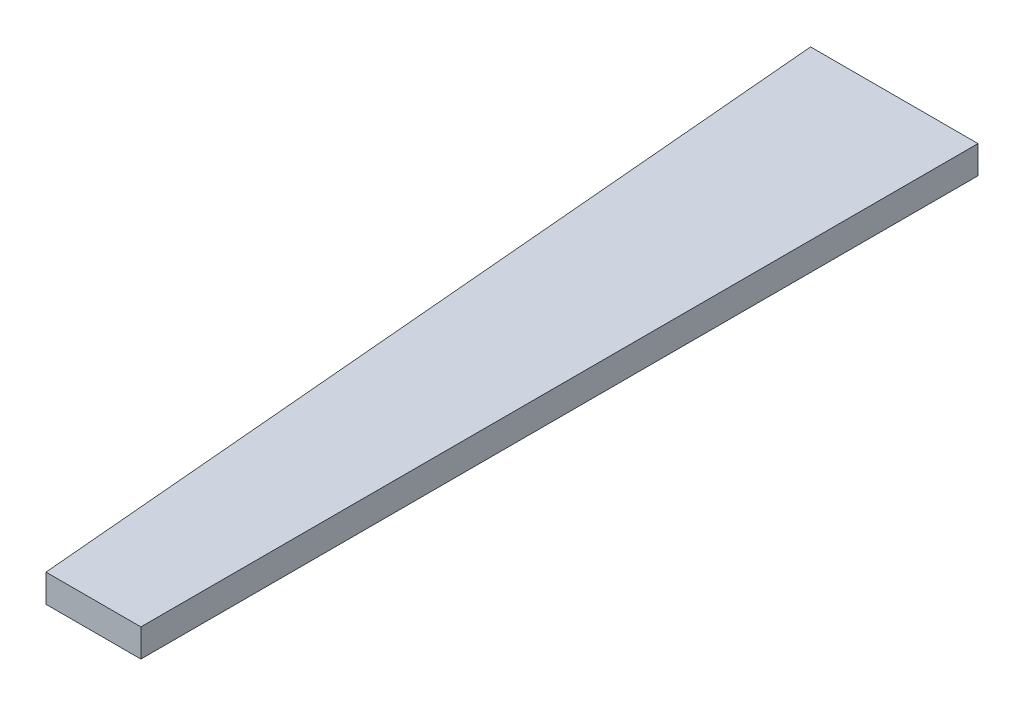
SolidWorks part; units mm, degrees
material "Cedar"
ref_plane "Front Plane" through (0, 0, 0) normal (0, 0, 1) x (1, 0, 0)
ref_plane "Top Plane" through (0, 0, 0) normal (0, 1, 0) x (1, 0, 0)
ref_plane "Right Plane" through (0, 0, 0) normal (1, 0, 0) x (0, 0, -1)
sketch "Sketch1" plane through (0, 0, 0) normal (0, 1, 0) x (1, 0, 0)
  line L0 (0, 0) -> (43.18, 0)
  line L1 (-23.7976, 0) -> (23.7976, 0) construction
  line L2 (43.18, 0) -> (43.18, 381)
  line L3 (43.18, 381) -> (-33.02, 381)
  line L4 (-33.02, 381) -> (0, 0)
  dimension "D1" = 381
  dimension "D2" = 76.2
  dimension "D3" = 43.18
extrude "Boss-Extrude1" add sketch "Sketch1" along normal blind 12.7
